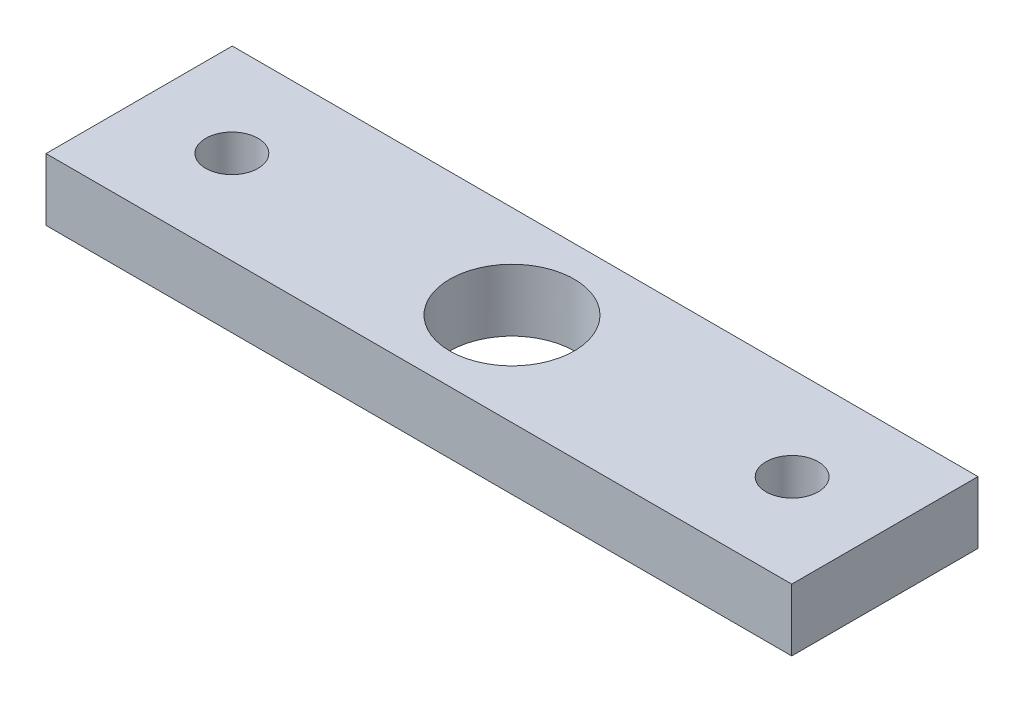
SolidWorks part; units mm, degrees
ref_plane "Front" through (0, 0, 0) normal (0, 0, 1) x (1, 0, 0)
ref_plane "Top" through (0, 0, 0) normal (0, 1, 0) x (1, 0, 0)
ref_plane "Right" through (0, 0, 0) normal (1, 0, 0) x (0, 0, -1)
sketch "Sketch1" plane through (0, 0, 0) normal (0, 1, 0) x (1, 0, 0)
  line L1 (-38.0365, -9.5) -> (38.0365, -9.5)
  line L2 (-38.0365, -9.5) -> (-38.0365, 9.5)
  line L3 (-38.0365, 9.5) -> (38.0365, 9.5)
  line L4 (38.0365, -9.5) -> (38.0365, 9.5)
  line L5 (-38.0365, -9.5) -> (38.0365, 9.5) construction
  line L6 (-38.0365, 9.5) -> (38.0365, -9.5) construction
  point P0 (0, 0)
  dimension "D1" = 76.073
  dimension "D2" = 19
extrude "Boss-Extrude1" add sketch "Sketch1" along normal blind 6.35
sketch "Sketch2" plane through (0, 6.35, 0) normal (0, 1, 0) x (1, 0, 0)
  circle A0 centre (0, 0) radius 6.35
  dimension "D1" = 12.7
extrude "Cut-Extrude2" cut sketch "Sketch2" against normal up to next
sketch "Sketch4" plane through (0, 6.35, 0) normal (0, 1, 0) x (1, 0, 0)
  line L0 (38.1, 0) -> (28.575, 0) construction
  line L1 (-38.1, 24.516) -> (38.1, 24.516) construction
  line L2 (-38.1, 24.516) -> (-38.1, -24.516) construction
  line L3 (-38.1, -24.516) -> (38.1, -24.516) construction
  line L4 (38.1, 24.516) -> (38.1, -24.516) construction
  line L5 (-38.1, 24.516) -> (38.1, -24.516) construction
  line L6 (-38.1, -24.516) -> (38.1, 24.516) construction
  line L7 (0, 9.5) -> (0, -9.5) construction
  line L8 (38.0365, 9.5) -> (-38.0365, 9.5) construction
  line L9 (-38.0365, -9.5) -> (38.0365, -9.5) construction
  circle A0 centre (28.575, 0) radius 2.665
  circle A1 centre (-28.575, 0) radius 2.665
  point P0 (0, 0)
  dimension "D3" = 5.33
  dimension "D1" = 76.2
  dimension "D2" = 9.525
extrude "Cut-Extrude3" cut sketch "Sketch4" against normal up to next
